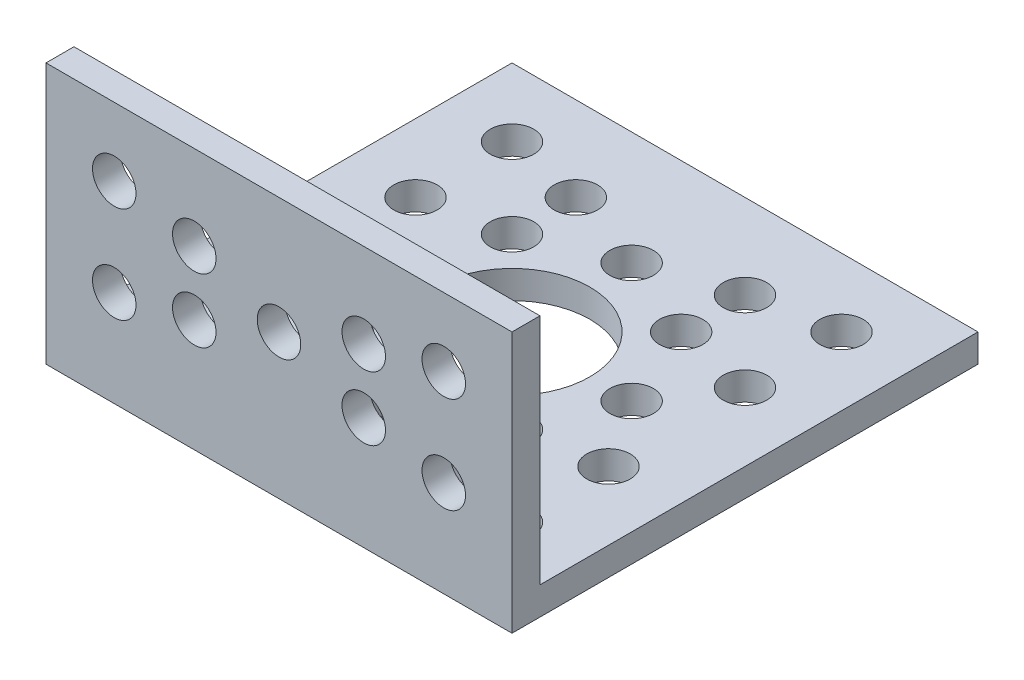
SolidWorks part; units mm, degrees
ref_plane "Front Plane" through (0, 0, 0) normal (0, 0, 1) x (1, 0, 0)
ref_plane "Top Plane" through (0, 0, 0) normal (0, 1, 0) x (1, 0, 0)
ref_plane "Right Plane" through (0, 0, 0) normal (1, 0, 0) x (0, 0, -1)
ref_plane "Plane1" through (0, 21.336, 0) normal (0, 1, 0) x (1, 0, 0)
sketch "Sketch1" plane through (0, 21.336, 0) normal (0, 1, 0) x (1, 0, 0)
  line L0 (19.05, -19.05) -> (19.05, 19.05)
  line L1 (19.05, 19.05) -> (-19.05, 19.05)
  line L2 (-19.05, 19.05) -> (-19.05, -19.05)
  line L3 (-19.05, -19.05) -> (19.05, -19.05)
extrude "Boss-Extrude1" add sketch "Sketch1" against normal blind 21.336
sketch "Sketch2" plane through (-19.05, 0, 0) normal (-1, 0, 0) x (0, 0, 1)
  line L0 (-19.05, 2.286) -> (16.764, 2.286)
  line L1 (16.764, 2.286) -> (16.764, 21.336)
  line L2 (16.764, 21.336) -> (-19.05, 21.336)
  line L3 (-19.05, 21.336) -> (-19.05, 2.286)
extrude "Cut-Extrude1" cut sketch "Sketch2" against normal through all
hole_wizard "Hole1" positions "Sketch4" profile "Sketch3" legacy
sketch "Sketch4" plane through (0, 0, 0) normal (0, -1, 0) x (-1, 0, 0)
  point P0 (0, 0)
sketch "Sketch3" plane through (0, 0, 0) normal (1, 0, 0) x (0, 0, -1)
  line L0 (0, 0) -> (0, 21.336)
  line L1 (0, 21.336) -> (6.3627, 21.336)
  line L2 (6.3627, 21.336) -> (6.3627, 0)
  line L3 (6.3627, 0) -> (0, 0)
  line L4 (0, 110) -> (0, -10) construction
  dimension "Diameter" = 12.7254
  dimension "Depth" = 21.336
hole_wizard "M3 Clearance Hole1" positions "Sketch6" profile "Sketch5" hole size "M3" standard "ANSI Metric"
sketch "Sketch6" plane through (0, 0, 0) normal (0, -1, 0) x (-1, 0, 0)
  point P0 (6.9148, -12.1352)
  point P1 (13.4704, 13.4704)
  point P2 (-13.4704, 13.4704)
  point P3 (0, -9.779)
  point P4 (6.9148, -6.9148)
  point P5 (9.779, 0)
  point P6 (6.9148, 6.9148)
  point P7 (0, 9.779)
  point P8 (-6.9148, 6.9148)
  point P9 (-9.779, 0)
  point P10 (-6.9148, -6.9148)
  point P11 (-13.4704, -5.5796)
  point P12 (-6.9148, -12.1352)
  point P13 (-13.4704, -13.4704)
  point P14 (-13.4704, 5.5796)
  point P15 (-6.9148, 12.1352)
  point P16 (13.4704, 5.5796)
  point P17 (6.9148, 12.1352)
  point P18 (13.4704, -5.5796)
  point P19 (13.4704, -13.4704)
sketch "Sketch5" plane through (-6.9148, 0, 12.1352) normal (1, 0, 0) x (0, 0, -1)
  line L0 (0, 0) -> (0, 21.336)
  line L1 (0, 21.336) -> (1.778, 21.336)
  line L2 (1.778, 21.336) -> (1.778, 0)
  line L5 (1.778, 0) -> (0, 0)
  line L11 (0, -6.35) -> (0, 107.95) construction
  dimension "Thru Hole Dia." = 3.556
  dimension "Thru Hole Depth" = 21.336
hole_wizard "M3 Clearance Hole2" positions "Sketch8" profile "Sketch7" hole size "M3" standard "ANSI Metric"
sketch "Sketch8" plane through (0, 0, 19.05) normal (0, 0, 1) x (1, 0, 0)
  point P0 (-6.9278, 14.4221)
  point P1 (13.4704, 7.8664)
  point P2 (13.4704, 15.7556)
  point P3 (6.9278, 9.1999)
  point P4 (6.9278, 14.4221)
  point P5 (0, 11.811)
  point P6 (-13.4704, 7.8664)
  point P7 (-13.4704, 15.7556)
  point P8 (-6.9278, 9.1999)
sketch "Sketch7" plane through (-6.9278, 14.4221, 19.05) normal (1, 0, 0) x (0, -1, 0)
  line L0 (0, 0) -> (0, 38.1)
  line L1 (0, 38.1) -> (1.778, 38.1)
  line L2 (1.778, 38.1) -> (1.778, 0)
  line L5 (1.778, 0) -> (0, 0)
  line L11 (0, -6.35) -> (0, 107.95) construction
  dimension "Thru Hole Dia." = 3.556
  dimension "Thru Hole Depth" = 38.1
